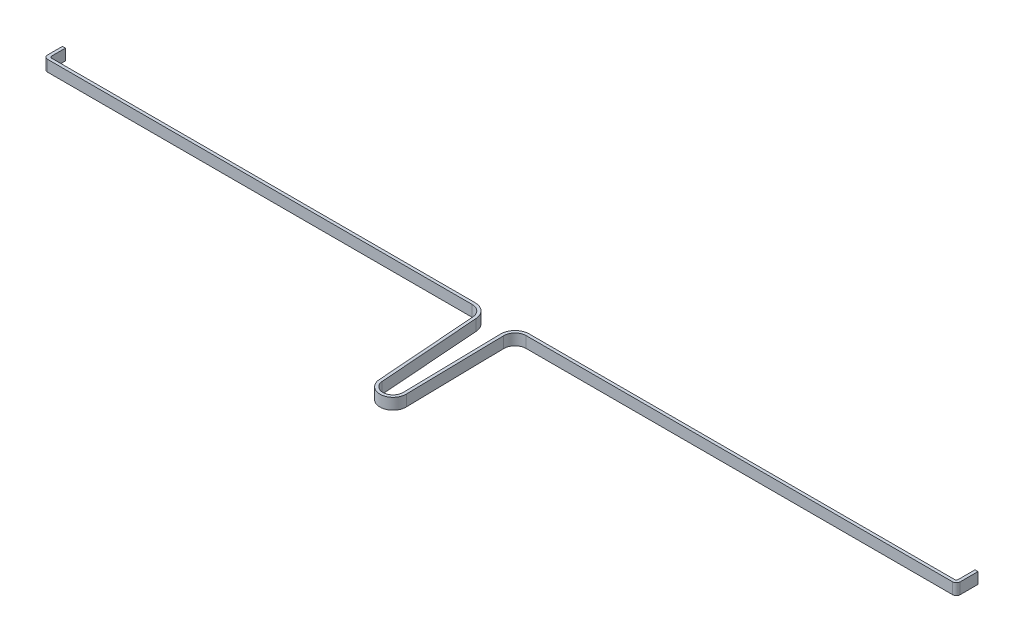
SolidWorks part; units mm, degrees
ref_plane "Front" through (0, 0, 0) normal (0, 0, 1) x (1, 0, 0)
ref_plane "Top" through (0, 0, 0) normal (0, 1, 0) x (1, 0, 0)
ref_plane "Right" through (0, 0, 0) normal (1, 0, 0) x (0, 0, -1)
sketch "Sketch1" plane through (0, 0, 0) normal (0, 1, 0) x (1, 0, 0)
  line L0 (-17, 59.5) -> (-247, 59.5)
  line L1 (12, 59.5) -> (243, 59.5)
  line L2 (6.0011, 53.3876) -> (6.9988, 0.1311)
  line L3 (-11.0164, 53.9434) -> (-6.9809, -0.5173)
  line L4 (12, 61.1) -> (243, 61.1)
  line L5 (4.4013, 53.3576) -> (5.3991, 0.1011)
  line L6 (-9.4208, 54.0616) -> (-5.3852, -0.399)
  line L7 (-17, 61.1) -> (-247, 61.1)
  line L8 (-247, 59.5) -> (-247, 69.5)
  line L9 (-247, 69.5) -> (-245.4, 69.5)
  line L10 (-245.4, 69.5) -> (-245.4, 59.5)
  line L11 (243, 59.5) -> (243, 71.1)
  line L12 (243, 71.1) -> (241.4, 71.1)
  line L13 (241.4, 71.1) -> (241.4, 59.5)
  arc A0 (-6.9809, -0.5173) -> (6.9988, 0.1311) centre (0, 0) ccw
  arc A1 (12, 59.5) -> (6.0011, 53.3876) centre (12, 53.5) ccw
  arc A2 (-11.0164, 53.9434) -> (-17, 59.5) centre (-17, 53.5) ccw
  arc A3 (12, 61.1) -> (4.4013, 53.3576) centre (12, 53.5) ccw
  arc A4 (-5.3852, -0.399) -> (5.3991, 0.1011) centre (0, 0) ccw
  arc A5 (-9.4208, 54.0616) -> (-17, 61.1) centre (-17, 53.5) ccw
  dimension "D1" = 14
  dimension "D2" = 12
  dimension "D3" = 12
  dimension "D4" = 17
  dimension "D5" = 53.5
  dimension "D6" = 12
  dimension "D7" = 230
  dimension "D8" = 490
  dimension "D9" = 1.6
  dimension "D10" = 1.6
  dimension "D11" = 10
  dimension "D12" = 10
  dimension "D13" = 1.6
extrude "Boss-Extrude1" add sketch "Sketch1" along normal blind 6 contours L10 L9 L8 L7 | L10 L7 L8 L0 | L6 A5 L7 L10 L0 A2 L3 A0 L2 A1 L1 L13 L4 A3 L5 A4 | L4 L13 L1 L11 | L12 L13 L4 L11
fillet "Fillet1" radius 1 2 edges at (-245.4, 3, -61.1) (241.4, 3, -61.1)
fillet "Fillet2" radius 2 2 edges at (243, 3, -59.5) (-247, 3, -59.5)
